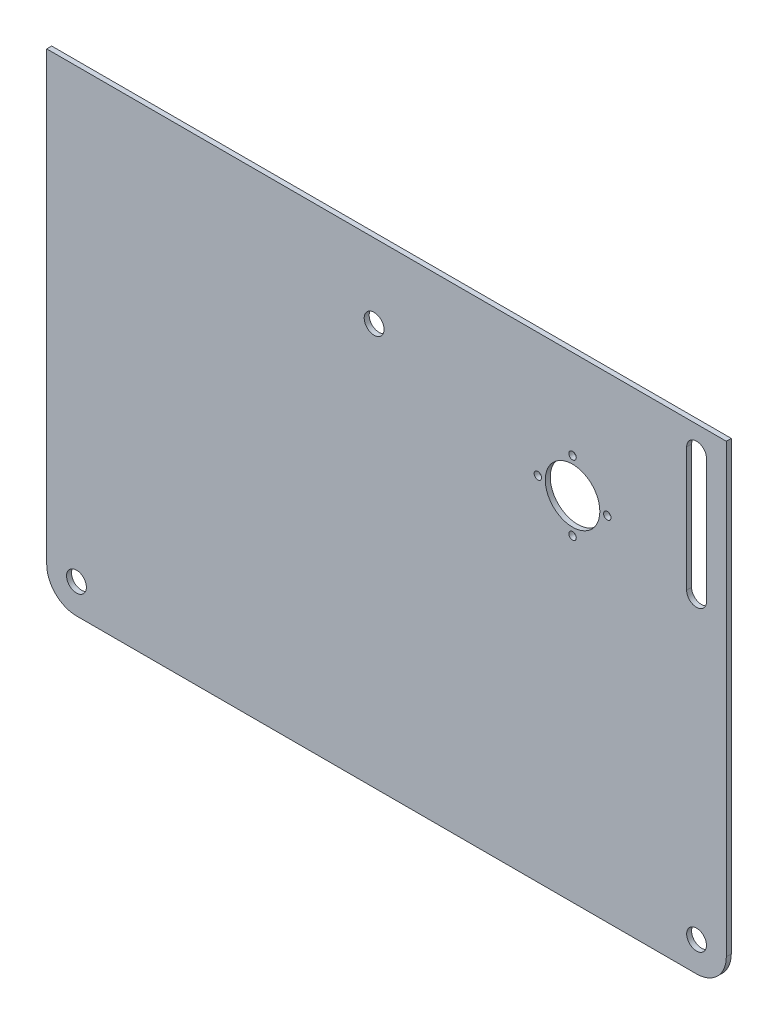
SolidWorks part; units mm, degrees
ref_plane "Front Plane" through (0, 0, 0) normal (0, 0, 1) x (1, 0, 0)
ref_plane "Top Plane" through (0, 0, 0) normal (0, 1, 0) x (1, 0, 0)
ref_plane "Right Plane" through (0, 0, 0) normal (1, 0, 0) x (0, 0, -1)
sketch "Sketch1" plane through (0, 0, 0) normal (0, 0, 1) x (1, 0, 0)
  line L0 (55, 0) -> (-55, 0) construction
  line L1 (0, 53.2731) -> (0, -38.9774) construction
  line L2 (0, -55) -> (0, 55) construction
  line L3 (-125, -12) -> (125, -12)
  line L4 (121, 120) -> (129, 120)
  line L5 (121, 120) -> (121, 170)
  line L6 (121, 170) -> (129, 170)
  line L7 (129, 120) -> (129, 170)
  line L8 (121, 120) -> (129, 170) construction
  line L9 (121, 170) -> (129, 120) construction
  line L10 (158.4448, 180) -> (-53.9982, 180)
  line L11 (137, 0) -> (137, 180)
  line L12 (137, 180) -> (158.4448, 180)
  line L13 (-53.9982, 180) -> (-137, 180)
  line L14 (-137, 180) -> (-137, 0)
  circle A0 centre (-125, 0) radius 4
  circle A1 centre (125, 0) radius 4
  circle A2 centre (125, 170) radius 4
  circle A3 centre (75, 130) radius 11
  circle A4 centre (-5, 150) radius 4
  circle A5 centre (125, 120) radius 4
  arc A6 (-125, -12) -> (-137, 0) centre (-125, 0) cw
  arc A7 (125, -12) -> (137, 0) centre (125, 0) ccw
  circle A8 centre (75, 130) radius 14 construction
  circle A9 centre (75, 144) radius 1.5
  circle A10 centre (89, 130) radius 1.5
  circle A11 centre (75, 116) radius 1.5
  circle A12 centre (61, 130) radius 1.5
  point P17 (125, 145)
  point P35 (89, 130)
  point P44 (75, 130)
  dimension "D2" = 8
  dimension "D4" = 22
  dimension "D11" = 12
  dimension "D13" = 12
  dimension "D14" = 28
  dimension "D15" = 3
  dimension "D1" = 250
  dimension "D3" = 250
  dimension "D5" = 120
  dimension "D6" = 150
  dimension "D7" = 130
  dimension "D8" = 200
  dimension "D9" = 145
  dimension "D10" = 50
  dimension "D12" = 10
  dimension "D16" = 4
extrude "Boss-Extrude1" add sketch "Sketch1" along normal blind 2 contours L3 A7 L11 L12 L10 L13 L14 A6 A0 A1 A3 A4 A5 L5 A2 L7
